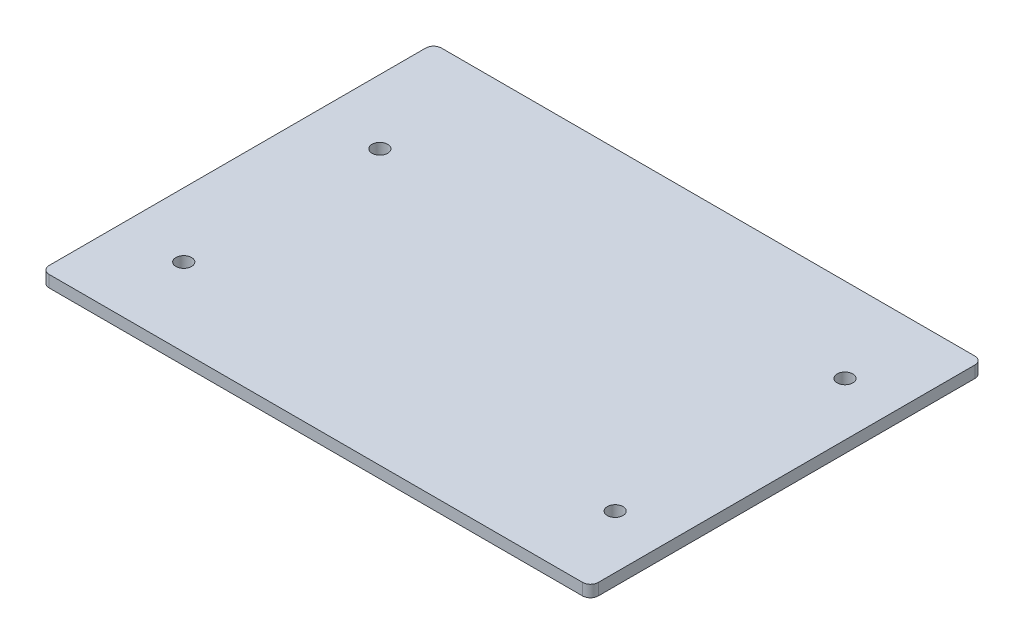
SolidWorks part; units mm, degrees
ref_plane "前视基准面" through (0, 0, 0) normal (0, 0, 1) x (1, 0, 0)
ref_plane "上视基准面" through (0, 0, 0) normal (0, 1, 0) x (1, 0, 0)
ref_plane "右视基准面" through (0, 0, 0) normal (1, 0, 0) x (0, 0, -1)
other "Configuration Table"
sketch "草图1" plane through (0, 0, 0) normal (0, 1, 0) x (1, 0, 0)
  line L0 (0, 0) -> (0, -50)
  line L1 (0, 0) -> (0, 50)
  line L2 (0, 50) -> (140, 50)
  line L3 (140, 50) -> (140, -50)
  line L4 (140, -50) -> (0, -50)
  line L5 (0, -50) -> (0, -30.1)
  line L6 (0, -30.1) -> (140, -30.1)
  line L7 (0, 50) -> (16.4, 50)
  line L8 (16.4, 50) -> (16.4, -50)
  line L9 (16.4, -30.1) -> (126.4, -30.1)
  line L10 (16.4, -30.1) -> (16.4, 19.9)
  line L11 (126.4, -30.1) -> (126.4, 28.5)
  circle A0 centre (16.4, -30.1) radius 2
  circle A1 centre (16.4, 19.9) radius 2
  circle A2 centre (126.4, 28.5) radius 2
  circle A3 centre (126.4, -30.1) radius 2
  dimension "D1" = 110
  dimension "D2" = 50
  dimension "D3" = 19.9
  dimension "D4" = 16.4
  dimension "D5" = 50
  dimension "D6" = 58.6
  dimension "D7" = 140
extrude "凸台-拉伸1" add sketch "草图1" along normal blind 3
fillet "圆角1" radius 2 4 edges at (0, 1.5, -50) (140, 1.5, -50) (140, 1.5, 50) (0, 1.5, 50)
